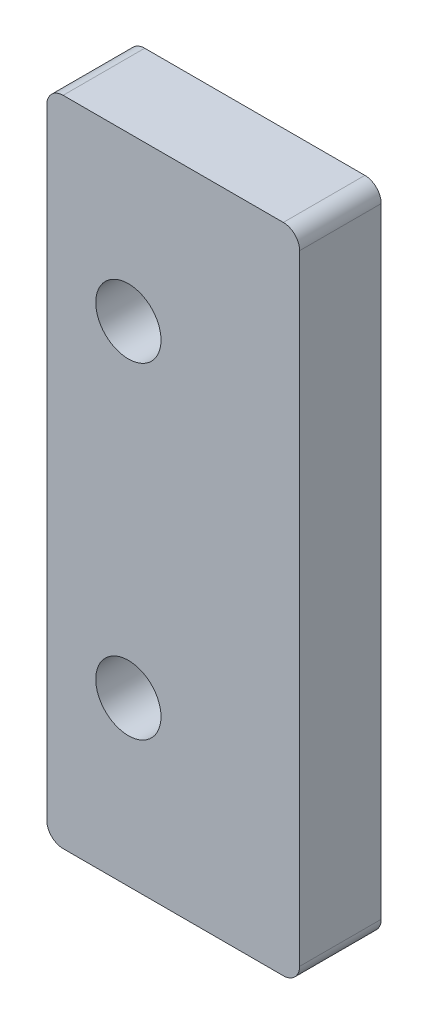
SolidWorks part; units mm, degrees
ref_plane "Front Plane" through (0, 0, 0) normal (0, 0, 1) x (1, 0, 0)
ref_plane "Top Plane" through (0, 0, 0) normal (0, 1, 0) x (1, 0, 0)
ref_plane "Right Plane" through (0, 0, 0) normal (1, 0, 0) x (0, 0, -1)
sketch "Sketch1" plane through (0, 0, 0) normal (0, 0, 1) x (1, 0, 0)
  line L0 (5, 40) -> (5, 0) construction
  line L1 (0, 0) -> (15.5, 0)
  line L2 (0, 0) -> (0, 40)
  line L3 (0, 40) -> (15.5, 40)
  line L4 (15.5, 0) -> (15.5, 40)
  circle A0 centre (5, 10) radius 2
  circle A1 centre (5, 30) radius 2
  dimension "D2" = 4
  dimension "D1" = 20
  dimension "D3" = 10
  dimension "D4" = 10
  dimension "D5" = 5
  dimension "D6" = 10.5
extrude "Boss-Extrude1" add sketch "Sketch1" along normal blind 5
fillet "Fillet1" radius 1 4 edges at (15.5, 0, 2.5) (0, 0, 2.5) (0, 40, 2.5) (15.5, 40, 2.5)
